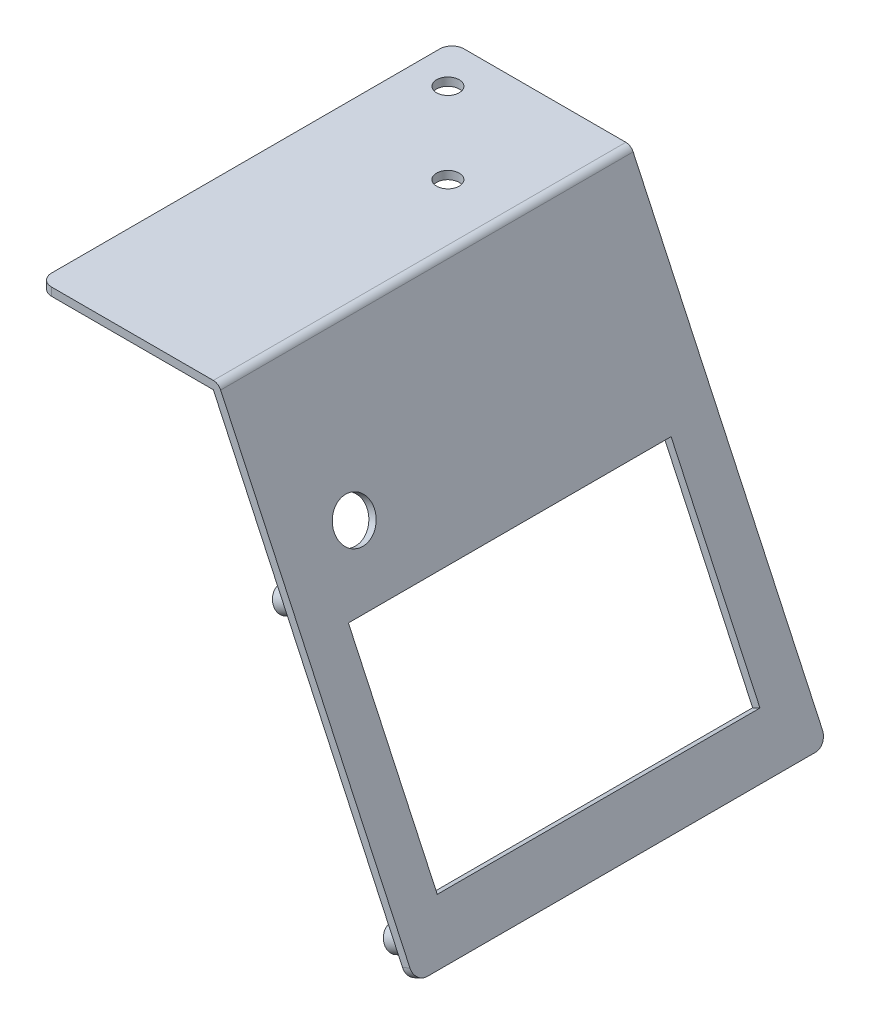
SolidWorks part; units mm, degrees
ref_plane "Alzado" through (0, 0, 0) normal (0, 0, 1) x (1, 0, 0)
ref_plane "Planta" through (0, 0, 0) normal (0, 1, 0) x (1, 0, 0)
ref_plane "Vista lateral" through (0, 0, 0) normal (1, 0, 0) x (0, 0, -1)
ref_plane "Plano1" through (0, 0, 0) normal (0, 0, -1) x (-1, 0, 0)
sketch "Croquis1" plane through (0, 0, 0) normal (0, 0, -1) x (-1, 0, 0)
  line L0 (-91.0626, -105.0706) -> (-43, -2)
  line L1 (-43, -2) -> (0, -2)
  line L2 (0, -2) -> (0, 0)
  line L3 (0, 0) -> (-44.2741, 0)
  line L4 (-44.2741, 0) -> (-92.8752, -104.2254)
  line L5 (-92.8752, -104.2254) -> (-91.0626, -105.0706)
extrude "Saliente-Extruir1" add sketch "Croquis1" against normal blind 102
sketch "Croquis2" plane through (36.3665, 16.958, 0) normal (0.9063, 0.4226, 0) x (0, 0, -1)
  line L0 (-11.5, -69.4056) -> (-91.3, -69.4056)
  line L1 (-91.3, -69.4056) -> (-91.3, -121.4056)
  line L2 (-91.3, -121.4056) -> (-11.5, -121.4056)
  line L3 (-11.5, -121.4056) -> (-11.5, -69.4056)
extrude "Cortar-Extruir1" cut sketch "Croquis2" against normal through all
ref_plane "Plano2" through (0, 0, 95.95) normal (0, 0, -1) x (-1, 0, 0)
sketch "Croquis3" plane through (0, 0, 95.95) normal (0, 0, -1) x (-1, 0, 0)
  line L0 (-56.0838, -46.6217) -> (-54.8159, -43.9027)
  line L1 (-54.8159, -43.9027) -> (-61.1601, -40.9444)
  line L2 (-61.1601, -40.9444) -> (-62.4279, -43.6633)
  line L3 (-62.4279, -43.6633) -> (-56.0838, -46.6217)
  line L4 (-53.7745, -44.3883) -> (-62.2015, -40.4588) construction
revolve "Revolución1" add sketch "Croquis3" angle 360 about L4
sketch "Croquis4" plane through (0, 0, 95.95) normal (0, 0, -1) x (-1, 0, 0)
  line L0 (-83.5117, -105.441) -> (-82.2438, -102.7221)
  line L1 (-82.2438, -102.7221) -> (-88.588, -99.7638)
  line L2 (-88.588, -99.7638) -> (-89.8559, -102.4827)
  line L3 (-89.8559, -102.4827) -> (-83.5117, -105.441)
  line L4 (-81.2024, -103.2077) -> (-89.6294, -99.2782) construction
revolve "Revolución2" add sketch "Croquis4" angle 360 about L4
ref_plane "Plano3" through (0, 0, 8.05) normal (0, 0, -1) x (-1, 0, 0)
sketch "Croquis5" plane through (0, 0, 8.05) normal (0, 0, -1) x (-1, 0, 0)
  line L0 (-83.5117, -105.441) -> (-82.2438, -102.7221)
  line L1 (-82.2438, -102.7221) -> (-88.588, -99.7638)
  line L2 (-88.588, -99.7638) -> (-89.8559, -102.4827)
  line L3 (-89.8559, -102.4827) -> (-83.5117, -105.441)
  line L4 (-81.2024, -103.2077) -> (-89.6294, -99.2782) construction
revolve "Revolución3" add sketch "Croquis5" angle 360 about L4
sketch "Croquis6" plane through (0, 0, 8.05) normal (0, 0, -1) x (-1, 0, 0)
  line L0 (-56.0838, -46.6217) -> (-54.8159, -43.9027)
  line L1 (-54.8159, -43.9027) -> (-61.1601, -40.9444)
  line L2 (-61.1601, -40.9444) -> (-62.4279, -43.6633)
  line L3 (-62.4279, -43.6633) -> (-56.0838, -46.6217)
  line L4 (-53.7745, -44.3883) -> (-62.2015, -40.4588) construction
revolve "Revolución4" add sketch "Croquis6" angle 360 about L4
hole_wizard "Diámetro de taladro Ø10.0 (10)1" positions "Croquis8" profile "Croquis7" hole size "Ø10.0" standard "Ansi Metric"
sketch "Croquis8" plane through (34.5539, 16.1127, 0) normal (-0.9063, -0.4226, 0) x (0, 0, 1)
  point P0 (83.1, -53.4056)
sketch "Croquis7" plane through (57.1241, -32.2892, 83.1) normal (0, 0, 1) x (0.4226, -0.9063, 0)
  line L0 (0, 0) -> (0, 46.0476)
  line L1 (0, 46.0476) -> (5, 46.0476)
  line L2 (5, 46.0476) -> (5, 0)
  line L5 (5, 0) -> (0, 0)
  line L11 (0, -6.35) -> (0, 107.95) construction
  dimension "Diámetro de taladro hasta el siguiente" = 10
  dimension "Profundidad de taladro hasta el siguiente" = 46.0476
hole_wizard "Diámetro de taladro Ø5.6 (5.6)1" positions "Croquis10" profile "Croquis9" hole size "Ø5.6" standard "Ansi Metric"
sketch "Croquis10" plane through (0, -2, 0) normal (0, -1, 0) x (-1, 0, 0)
  point P0 (-29, -30)
  point P1 (-9, -10)
sketch "Croquis9" plane through (29, -2, 30) normal (1, 0, 0) x (0, 0, -1)
  line L0 (0, 0) -> (0, 2)
  line L1 (0, 2) -> (2.8, 2)
  line L2 (2.8, 2) -> (2.8, 0)
  line L5 (2.8, 0) -> (0, 0)
  line L11 (0, -6.35) -> (0, 107.95) construction
  dimension "Diámetro de taladro hasta el siguiente" = 5.6
  dimension "Profundidad de taladro hasta el siguiente" = 2
hole_wizard "Diámetro de taladro Ø2.7 (2.7)1" positions "Croquis12" profile "Croquis11" hole size "Ø2.7" standard "Ansi Metric"
sketch "Croquis12" plane through (28.2097, 13.1544, 0) normal (-0.9063, -0.4226, 0) x (0, 0, 1)
  point P0 (8.05, -62.9556)
  point P1 (8.05, -127.8556)
  point P2 (95.95, -127.8556)
  point P3 (95.95, -62.9556)
sketch "Croquis11" plane through (54.8159, -43.9027, 8.05) normal (0, 0, 1) x (0.4226, -0.9063, 0)
  line L0 (0, 0) -> (0, 7)
  line L1 (0, 7) -> (1.35, 7)
  line L2 (1.35, 7) -> (1.35, 0)
  line L5 (1.35, 0) -> (0, 0)
  line L10 (0, 7) -> (-1.35, 7) construction
  line L11 (0, -6.35) -> (0, 107.95) construction
  dimension "Diámetro de taladro" = 2.7
  dimension "Profundidad de taladro" = 7
  dimension "Ángulo de perforador" = 180
fillet "Redondeo1" radius 2 1 edges at (44.2741, 0, 51)
fillet "Redondeo2" radius 3 4 edges at (91.9689, -104.648, 102) (0, -1, 0) (0, -1, 102) (91.9689, -104.648, 0)
